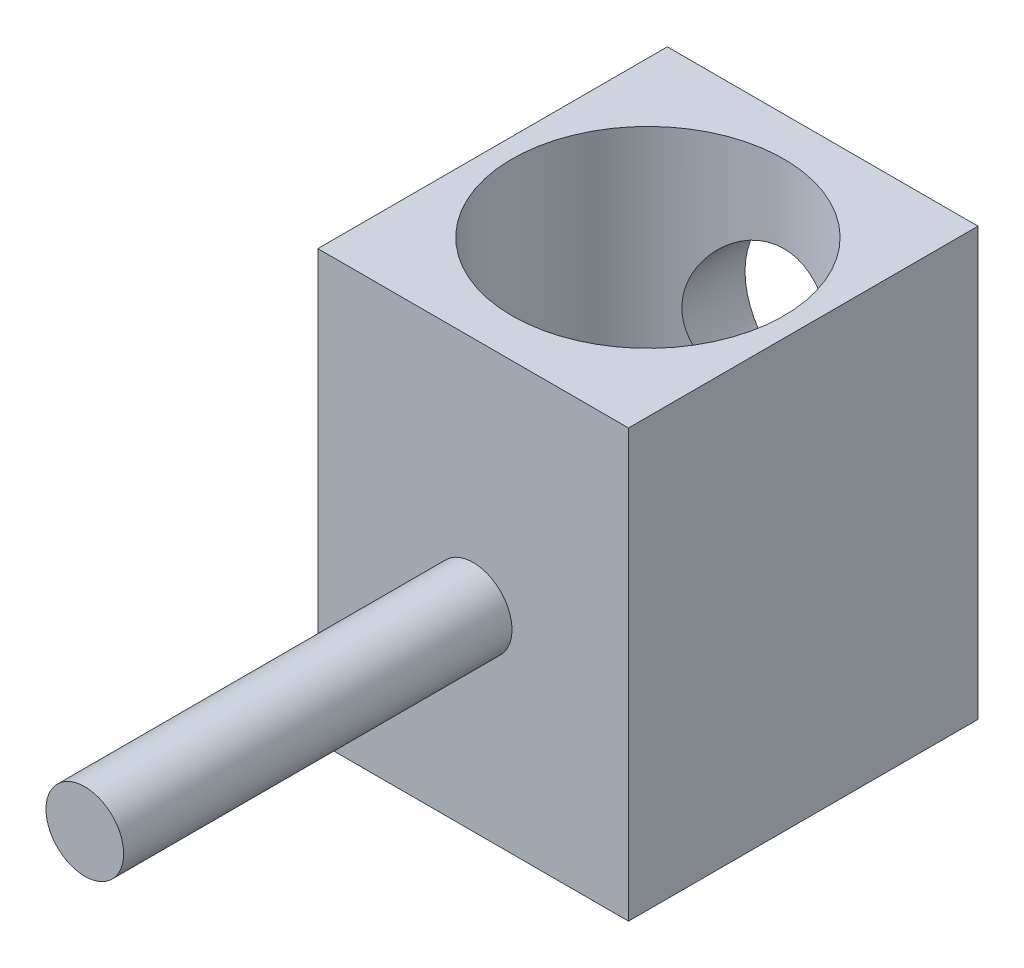
SolidWorks part; units mm, degrees
ref_plane "Front Plane" through (0, 0, 0) normal (0, 0, 1) x (1, 0, 0)
ref_plane "Top Plane" through (0, 0, 0) normal (0, 1, 0) x (1, 0, 0)
ref_plane "Right Plane" through (0, 0, 0) normal (1, 0, 0) x (0, 0, -1)
sketch "Sketch4" plane through (0, 0, 0) normal (0, 1, 0) x (1, 0, 0)
  line L1 (-2, -2.25) -> (2, -2.25)
  line L2 (-2, -2.25) -> (-2, 2.25)
  line L3 (-2, 2.25) -> (2, 2.25)
  line L4 (2, -2.25) -> (2, 2.25)
  line L5 (-2, -2.25) -> (2, 2.25) construction
  line L6 (-2, 2.25) -> (2, -2.25) construction
  point P0 (0, 0)
  dimension "D1" = 4
  dimension "D2" = 4.5
extrude "Boss-Extrude1" add sketch "Sketch4" along normal blind 5.5
sketch "Sketch5" plane through (0, 0, 2.25) normal (0, 0, 1) x (1, 0, 0)
  line L0 (-2, 5.5) -> (2, 5.5) construction
  line L1 (-2, 5.5) -> (-2, 0) construction
  line L3 (2, 5.5) -> (2, 0) construction
  circle A0 centre (0, 2.5) radius 0.5
  dimension "D1" = 3
  dimension "D2" = 2
  dimension "D3" = 2
extrude "Boss-Extrude2" add sketch "Sketch5" along normal blind 5
sketch "Sketch6" plane through (0, 5.5, 0) normal (0, 1, 0) x (1, 0, 0)
  circle A0 centre (0, 0) radius 1.75
extrude "Cut-Extrude1" cut sketch "Sketch6" against normal blind 5
sketch "Sketch7" plane through (0, 0, -2.25) normal (0, 0, -1) x (-1, 0, 0)
  line L0 (-2, 5.5) -> (2, 5.5) construction
  line L1 (-2, 5.5) -> (-2, 0) construction
  circle A0 centre (0, 3.5) radius 1
  dimension "D1" = 2
  dimension "D2" = 2
  dimension "D3" = 2
extrude "Cut-Extrude2" cut sketch "Sketch7" against normal blind 2
